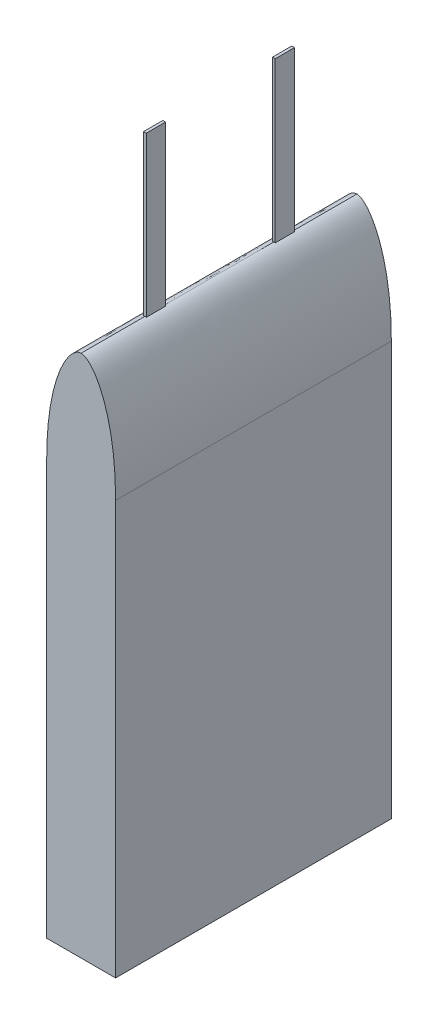
SolidWorks part; units mm, degrees
ref_plane "Front Plane" through (0, 0, 0) normal (0, 0, 1) x (1, 0, 0)
ref_plane "Top Plane" through (0, 0, 0) normal (0, 1, 0) x (1, 0, 0)
ref_plane "Right Plane" through (0, 0, 0) normal (1, 0, 0) x (0, 0, -1)
sketch "Sketch1" plane through (0, 0, 0) normal (1, 0, 0) x (0, 0, -1)
  line L1 (-10, 15) -> (10, 15)
  line L2 (-10, 15) -> (-10, -15)
  line L3 (-10, -15) -> (10, -15)
  line L4 (10, 15) -> (10, -15)
  line L5 (-10, 15) -> (10, -15) construction
  line L6 (-10, -15) -> (10, 15) construction
  point P0 (0, 0)
  dimension "D1" = 20
  dimension "D2" = 30
extrude "Boss-Extrude1" add sketch "Sketch1" along normal blind 5
sketch "Sketch3" plane through (0, 0, 0) normal (0, 0, 1) x (1, 0, 0)
  line L0 (2.5, 15) -> (2.5, 22.9979) construction
  line L1 (5, 15) -> (0, 15) construction
  line L2 (0, 15) -> (5, 15)
  spline S0 degree 3 poles (2.5, 22.9979) (3.3366, 22.9996) (5.0058, 20.5485) (5, 15) knots 0 0 0 0 1 1 1 1
  spline S1 degree 3 poles (2.5, 22.9979) (1.6634, 22.9996) (-0.0058, 20.5485) (0, 15) knots 0 0 0 0 1 1 1 1
extrude "Boss-Extrude2" add sketch "Sketch3" along normal blind 10 and the other way blind 10
ref_plane "Plane1" through (2.5, 0, 0) normal (1, 0, 0) x (0, 0, -1)
sketch "Sketch4" plane through (2.5, 0, 0) normal (1, 0, 0) x (0, 0, -1)
  line L0 (0, 22.9979) -> (0, 17.1945) construction
  line L1 (10, 22.9979) -> (-10, 22.9979) construction
  line L2 (-3.9752, 17.0445) -> (-5.3753, 34.5564) construction
  line L3 (3.9752, 34.5564) -> (5.3753, 34.5564)
  line L4 (3.9752, 34.5564) -> (3.9752, 17.0445)
  line L5 (3.9752, 17.0445) -> (5.3753, 17.0445)
  line L6 (5.3753, 34.5564) -> (5.3753, 17.0445)
  line L7 (3.9752, 34.5564) -> (5.3753, 17.0445) construction
  line L8 (3.9752, 17.0445) -> (5.3753, 34.5564) construction
  line L9 (-3.9752, 34.5564) -> (-5.3753, 17.0445) construction
  line L10 (-5.3753, 34.5564) -> (-5.3753, 17.0445)
  line L11 (-3.9752, 17.0445) -> (-5.3753, 17.0445)
  line L12 (-3.9752, 34.5564) -> (-3.9752, 17.0445)
  line L13 (-3.9752, 34.5564) -> (-5.3753, 34.5564)
  point P5 (4.6752, 25.8004)
  point P14 (-4.6752, 25.8004)
extrude "Boss-Extrude3" add sketch "Sketch4" along normal blind 0.1 and the other way blind 0.1
